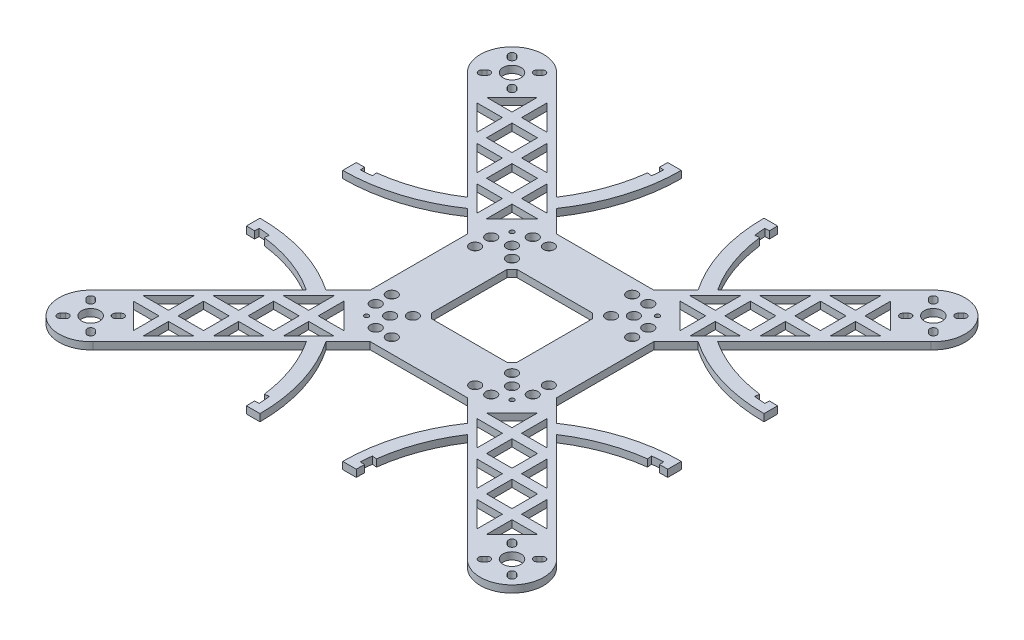
SolidWorks part; units mm, degrees
material "Baltic Birch Plywood"
ref_plane "Front Plane" through (0, 0, 0) normal (0, 0, 1) x (1, 0, 0)
ref_plane "Top Plane" through (0, 0, 0) normal (0, 1, 0) x (1, 0, 0)
ref_plane "Right Plane" through (0, 0, 0) normal (1, 0, 0) x (0, 0, -1)
sketch "Sketch1" plane through (0, 0, 0) normal (0, 1, 0) x (1, 0, 0)
  line L1 (-41.29, -41.29) -> (41.29, -41.29)
  line L2 (-41.29, -41.29) -> (-41.29, 41.29)
  line L3 (-41.29, 41.29) -> (41.29, 41.29)
  line L4 (41.29, -41.29) -> (41.29, 41.29)
  line L5 (-41.29, -41.29) -> (41.29, 41.29) construction
  line L6 (-41.29, 41.29) -> (41.29, -41.29) construction
  point P0 (0, 0)
  dimension "D1" = 82.58
  dimension "D2" = 82.58
extrude "Center Square" add sketch "Sketch1" along normal blind 3.175
sketch "Sketch2" plane through (0, 3.175, 0) normal (0, 1, 0) x (1, 0, 0)
  line L1 (-18.935, -18.935) -> (18.935, -18.935)
  line L2 (-18.935, -18.935) -> (-18.935, 18.935)
  line L3 (-18.935, 18.935) -> (18.935, 18.935)
  line L4 (18.935, -18.935) -> (18.935, 18.935)
  line L5 (-18.935, -18.935) -> (18.935, 18.935) construction
  line L6 (-18.935, 18.935) -> (18.935, -18.935) construction
  point P0 (0, 0)
  dimension "D1" = 37.87
  dimension "D2" = 37.87
extrude "Square Hole" cut sketch "Sketch2" against normal blind 3.175
sketch "Sketch3" plane through (0, 3.175, 0) normal (0, 1, 0) x (1, 0, 0)
  line L0 (0, 0) -> (41.29, 41.29) construction
  line L1 (0, 0) -> (0, 21.955) construction
  line L2 (0, 21.955) -> (21.955, 21.955) construction
  circle A0 centre (21.955, 21.955) radius 2.375
  circle A1 centre (26.9931, 26.9931) radius 2.375
  circle A2 centre (21.955, -21.955) radius 2.375
  circle A3 centre (26.9931, -26.9931) radius 2.375
  circle A4 centre (-21.955, -21.955) radius 2.375
  circle A5 centre (-26.9931, -26.9931) radius 2.375
  circle A6 centre (-21.955, 21.955) radius 2.375
  circle A7 centre (-26.9931, 26.9931) radius 2.375
  point P24 (0, 0)
  dimension "D2" = 4.75
  dimension "D3" = 4.75
  dimension "D1" = 21.955
  dimension "D4" = 7.125
  dimension "D5" = 4
extrude "Power Board Mounting Holes" cut sketch "Sketch3" against normal blind 3.175
sketch "Sketch4" plane through (0, 3.175, 0) normal (0, 1, 0) x (1, 0, 0)
  line L0 (0, 0) -> (18.935, 18.935) construction
  line L1 (16.6899, 18.935) -> (18.935, 16.6899)
  line L2 (18.935, 18.935) -> (17.8125, 17.8125) construction
  line L3 (18.935, -18.935) -> (18.935, 18.935) construction
  line L5 (18.935, 16.6899) -> (18.935, 18.935)
  line L6 (18.935, 18.935) -> (16.6899, 18.935)
  line L7 (18.935, -16.6899) -> (16.6899, -18.935)
  line L9 (16.6899, -18.935) -> (18.935, -18.935)
  line L10 (18.935, -18.935) -> (18.935, -16.6899)
  line L11 (18.935, -18.935) -> (17.8125, -17.8125) construction
  line L12 (-16.6899, -18.935) -> (-18.935, -16.6899)
  line L13 (-18.935, -16.6899) -> (-18.935, -18.935)
  line L14 (-18.935, -18.935) -> (-16.6899, -18.935)
  line L15 (-18.935, -18.935) -> (-17.8125, -17.8125) construction
  line L16 (-18.935, 16.6899) -> (-16.6899, 18.935)
  line L17 (-16.6899, 18.935) -> (-18.935, 18.935)
  line L18 (-18.935, 18.935) -> (-18.935, 16.6899)
  line L19 (-18.935, 18.935) -> (-17.8125, 17.8125) construction
  point P9 (17.8125, 17.8125)
  point P11 (17.8125, 17.8125)
  point P18 (17.8125, -17.8125)
  point P19 (17.8125, -17.8125)
  point P24 (-17.8125, -17.8125)
  point P25 (-17.8125, -17.8125)
  point P30 (-17.8125, 17.8125)
  point P31 (-17.8125, 17.8125)
  point P32 (0, 0)
  dimension "D1" = 1.5875
  dimension "D2" = 4
extrude "Square Hole Diagonals" add sketch "Sketch4" against normal blind 3.175
sketch "Sketch5" plane through (0, 3.175, 0) normal (0, 1, 0) x (1, 0, 0)
  line L0 (0, 0) -> (41.29, 41.29) construction
  line L1 (0, 0) -> (0, 32.22) construction
  line L3 (0, 32.22) -> (32.22, 32.22) construction
  circle A0 centre (32.22, 32.22) radius 1
  circle A1 centre (32.22, -32.22) radius 1
  circle A2 centre (-32.22, -32.22) radius 1
  circle A3 centre (-32.22, 32.22) radius 1
  point P16 (0, 0)
  dimension "D2" = 2
  dimension "D1" = 32.22
  dimension "D3" = 4
extrude "Electronics Board Mounting Holes" cut sketch "Sketch5" against normal through all
sketch "Sketch6" plane through (0, 3.175, 0) normal (0, 1, 0) x (1, 0, 0)
  line L0 (0, 0) -> (41.29, 0) construction
  line L1 (41.29, -41.29) -> (41.29, 41.29) construction
  line L2 (41.29, 0) -> (34.79, 0) construction
  line L3 (34.79, 0) -> (34.79, 18.46) construction
  line L4 (34.79, 18.46) -> (34.79, 25.585) construction
  circle A0 centre (34.79, 18.46) radius 2.375
  circle A1 centre (34.79, 25.585) radius 2.375
  circle A2 centre (34.79, -25.585) radius 2.375
  circle A3 centre (34.79, -18.46) radius 2.375
  circle A4 centre (25.585, -34.79) radius 2.375
  circle A5 centre (18.46, -34.79) radius 2.375
  circle A6 centre (-18.46, -34.79) radius 2.375
  circle A7 centre (-25.585, -34.79) radius 2.375
  circle A8 centre (-34.79, -25.585) radius 2.375
  circle A9 centre (-34.79, -18.46) radius 2.375
  circle A10 centre (-34.79, 18.46) radius 2.375
  circle A11 centre (-34.79, 25.585) radius 2.375
  circle A12 centre (-25.585, 34.79) radius 2.375
  circle A13 centre (-18.46, 34.79) radius 2.375
  circle A14 centre (18.46, 34.79) radius 2.375
  circle A15 centre (25.585, 34.79) radius 2.375
  point P41 (0, 0)
  dimension "D3" = 4.75
  dimension "D4" = 7.125
  dimension "D5" = 4.75
  dimension "D1" = 6.5
  dimension "D2" = 18.46
  dimension "D6" = 4
extrude "IR Sensor Mounting Holes" cut sketch "Sketch6" against normal through all
sketch "Sketch7" plane through (0, 3.175, 0) normal (0, 1, 0) x (1, 0, 0)
  line L0 (33.22, 33.22) -> (93.3241, 93.3241) construction
  line L1 (82.9452, 102.7197) -> (21.5154, 41.29)
  line L2 (41.29, 41.29) -> (-41.29, 41.29) construction
  line L4 (21.5154, 41.29) -> (41.29, 41.29)
  line L5 (41.29, 41.29) -> (41.29, 21.5154)
  line L6 (41.29, -41.29) -> (41.29, 41.29) construction
  line L7 (41.29, 21.5154) -> (102.7197, 82.9452)
  line L8 (102.7197, -82.9452) -> (41.29, -21.5154)
  line L9 (33.22, 33.22) -> (0, 0) construction
  line L10 (21.5154, -41.29) -> (82.9452, -102.7197)
  line L11 (33.22, -33.22) -> (93.3241, -93.3241) construction
  line L12 (41.29, -21.5154) -> (41.29, -41.29)
  line L13 (41.29, -41.29) -> (21.5154, -41.29)
  line L14 (-82.9452, -102.7197) -> (-21.5154, -41.29)
  line L15 (-41.29, -21.5154) -> (-102.7197, -82.9452)
  line L16 (-33.22, -33.22) -> (-93.3241, -93.3241) construction
  line L17 (-21.5154, -41.29) -> (-41.29, -41.29)
  line L18 (-41.29, -41.29) -> (-41.29, -21.5154)
  line L19 (-102.7197, 82.9452) -> (-41.29, 21.5154)
  line L20 (-21.5154, 41.29) -> (-82.9452, 102.7197)
  line L21 (-33.22, 33.22) -> (-93.3241, 93.3241) construction
  line L22 (-41.29, 21.5154) -> (-41.29, 41.29)
  line L23 (-41.29, 41.29) -> (-21.5154, 41.29)
  arc A0 (102.7197, 82.9452) -> (82.9452, 102.7197) centre (93.3241, 93.3241) ccw
  arc A1 (82.9452, -102.7197) -> (102.7197, -82.9452) centre (93.3241, -93.3241) ccw
  arc A2 (-102.7197, -82.9452) -> (-82.9452, -102.7197) centre (-93.3241, -93.3241) ccw
  arc A3 (-82.9452, 102.7197) -> (-102.7197, 82.9452) centre (-93.3241, 93.3241) ccw
  point P38 (0, 0)
  point P45 (0, 0)
  dimension "D2" = 28
  dimension "D1" = 85
extrude "Propeller Arms" add sketch "Sketch7" against normal blind 3.175
sketch "Sketch8" plane through (0, 3.175, 0) normal (0, 1, 0) x (1, 0, 0)
  line L0 (93.3241, 93.3241) -> (103.2236, 103.2236) construction
  line L1 (93.3241, 93.3241) -> (98.9102, 98.9102) construction
  line L2 (93.3241, 93.3241) -> (99.9709, 99.9709) construction
  line L3 (98.9102, 98.9102) -> (99.9709, 99.9709) construction
  line L4 (97.8496, 99.9709) -> (98.9102, 101.0315)
  line L5 (99.9709, 97.8496) -> (101.0315, 98.9102)
  line L6 (98.9102, 87.7379) -> (99.9709, 86.6773) construction
  line L7 (99.9709, 88.7986) -> (101.0315, 87.7379)
  line L8 (97.8496, 86.6773) -> (98.9102, 85.6166)
  line L9 (87.7379, 87.7379) -> (86.6773, 86.6773) construction
  line L10 (88.7986, 86.6773) -> (87.7379, 85.6166)
  line L11 (86.6773, 88.7986) -> (85.6166, 87.7379)
  line L12 (87.7379, 98.9102) -> (86.6773, 99.9709) construction
  line L13 (86.6773, 97.8496) -> (85.6166, 98.9102)
  line L14 (88.7986, 99.9709) -> (87.7379, 101.0315)
  line L15 (93.3241, -93.3241) -> (103.2236, -103.2236) construction
  line L16 (93.3241, -93.3241) -> (98.9102, -98.9102) construction
  line L17 (93.3241, -93.3241) -> (99.9709, -99.9709) construction
  line L18 (98.9102, -98.9102) -> (99.9709, -99.9709) construction
  line L19 (99.9709, -97.8496) -> (101.0315, -98.9102)
  line L20 (97.8496, -99.9709) -> (98.9102, -101.0315)
  line L21 (87.7379, -98.9102) -> (86.6773, -99.9709) construction
  line L22 (88.7986, -99.9709) -> (87.7379, -101.0315)
  line L23 (86.6773, -97.8496) -> (85.6166, -98.9102)
  line L24 (87.7379, -87.7379) -> (86.6773, -86.6773) construction
  line L25 (86.6773, -88.7986) -> (85.6166, -87.7379)
  line L26 (88.7986, -86.6773) -> (87.7379, -85.6166)
  line L27 (98.9102, -87.7379) -> (99.9709, -86.6773) construction
  line L28 (97.8496, -86.6773) -> (98.9102, -85.6166)
  line L29 (99.9709, -88.7986) -> (101.0315, -87.7379)
  line L30 (-93.3241, -93.3241) -> (-103.2236, -103.2236) construction
  line L31 (-93.3241, -93.3241) -> (-98.9102, -98.9102) construction
  line L32 (-93.3241, -93.3241) -> (-99.9709, -99.9709) construction
  line L33 (-98.9102, -98.9102) -> (-99.9709, -99.9709) construction
  line L34 (-97.8496, -99.9709) -> (-98.9102, -101.0315)
  line L35 (-99.9709, -97.8496) -> (-101.0315, -98.9102)
  line L36 (-98.9102, -87.7379) -> (-99.9709, -86.6773) construction
  line L37 (-99.9709, -88.7986) -> (-101.0315, -87.7379)
  line L38 (-97.8496, -86.6773) -> (-98.9102, -85.6166)
  line L39 (-87.7379, -87.7379) -> (-86.6773, -86.6773) construction
  line L40 (-88.7986, -86.6773) -> (-87.7379, -85.6166)
  line L41 (-86.6773, -88.7986) -> (-85.6166, -87.7379)
  line L42 (-87.7379, -98.9102) -> (-86.6773, -99.9709) construction
  line L43 (-86.6773, -97.8496) -> (-85.6166, -98.9102)
  line L44 (-88.7986, -99.9709) -> (-87.7379, -101.0315)
  line L45 (-93.3241, 93.3241) -> (-103.2236, 103.2236) construction
  line L46 (-93.3241, 93.3241) -> (-98.9102, 98.9102) construction
  line L47 (-93.3241, 93.3241) -> (-99.9709, 99.9709) construction
  line L48 (-98.9102, 98.9102) -> (-99.9709, 99.9709) construction
  line L49 (-99.9709, 97.8496) -> (-101.0315, 98.9102)
  line L50 (-97.8496, 99.9709) -> (-98.9102, 101.0315)
  line L51 (-87.7379, 98.9102) -> (-86.6773, 99.9709) construction
  line L52 (-88.7986, 99.9709) -> (-87.7379, 101.0315)
  line L53 (-86.6773, 97.8496) -> (-85.6166, 98.9102)
  line L54 (-87.7379, 87.7379) -> (-86.6773, 86.6773) construction
  line L55 (-86.6773, 88.7986) -> (-85.6166, 87.7379)
  line L56 (-88.7986, 86.6773) -> (-87.7379, 85.6166)
  line L57 (-98.9102, 87.7379) -> (-99.9709, 86.6773) construction
  line L58 (-97.8496, 86.6773) -> (-98.9102, 85.6166)
  line L59 (-99.9709, 88.7986) -> (-101.0315, 87.7379)
  circle A0 centre (93.3241, 93.3241) radius 4
  arc A1 (102.7197, 82.9452) -> (82.9452, 102.7197) centre (93.3241, 93.3241) ccw construction
  arc A2 (97.8496, 99.9709) -> (99.9709, 97.8496) centre (98.9102, 98.9102) ccw
  arc A3 (101.0315, 98.9102) -> (98.9102, 101.0315) centre (99.9709, 99.9709) ccw
  arc A4 (99.9709, 88.7986) -> (97.8496, 86.6773) centre (98.9102, 87.7379) ccw
  arc A5 (98.9102, 85.6166) -> (101.0315, 87.7379) centre (99.9709, 86.6773) ccw
  arc A6 (88.7986, 86.6773) -> (86.6773, 88.7986) centre (87.7379, 87.7379) ccw
  arc A7 (85.6166, 87.7379) -> (87.7379, 85.6166) centre (86.6773, 86.6773) ccw
  arc A8 (86.6773, 97.8496) -> (88.7986, 99.9709) centre (87.7379, 98.9102) ccw
  arc A9 (87.7379, 101.0315) -> (85.6166, 98.9102) centre (86.6773, 99.9709) ccw
  circle A10 centre (93.3241, -93.3241) radius 4
  arc A11 (99.9709, -97.8496) -> (97.8496, -99.9709) centre (98.9102, -98.9102) ccw
  arc A12 (98.9102, -101.0315) -> (101.0315, -98.9102) centre (99.9709, -99.9709) ccw
  arc A13 (88.7986, -99.9709) -> (86.6773, -97.8496) centre (87.7379, -98.9102) ccw
  arc A14 (85.6166, -98.9102) -> (87.7379, -101.0315) centre (86.6773, -99.9709) ccw
  arc A15 (86.6773, -88.7986) -> (88.7986, -86.6773) centre (87.7379, -87.7379) ccw
  arc A16 (87.7379, -85.6166) -> (85.6166, -87.7379) centre (86.6773, -86.6773) ccw
  arc A17 (97.8496, -86.6773) -> (99.9709, -88.7986) centre (98.9102, -87.7379) ccw
  arc A18 (101.0315, -87.7379) -> (98.9102, -85.6166) centre (99.9709, -86.6773) ccw
  circle A19 centre (-93.3241, -93.3241) radius 4
  arc A20 (-97.8496, -99.9709) -> (-99.9709, -97.8496) centre (-98.9102, -98.9102) ccw
  arc A21 (-101.0315, -98.9102) -> (-98.9102, -101.0315) centre (-99.9709, -99.9709) ccw
  arc A22 (-99.9709, -88.7986) -> (-97.8496, -86.6773) centre (-98.9102, -87.7379) ccw
  arc A23 (-98.9102, -85.6166) -> (-101.0315, -87.7379) centre (-99.9709, -86.6773) ccw
  arc A24 (-88.7986, -86.6773) -> (-86.6773, -88.7986) centre (-87.7379, -87.7379) ccw
  arc A25 (-85.6166, -87.7379) -> (-87.7379, -85.6166) centre (-86.6773, -86.6773) ccw
  arc A26 (-86.6773, -97.8496) -> (-88.7986, -99.9709) centre (-87.7379, -98.9102) ccw
  arc A27 (-87.7379, -101.0315) -> (-85.6166, -98.9102) centre (-86.6773, -99.9709) ccw
  circle A28 centre (-93.3241, 93.3241) radius 4
  arc A29 (-99.9709, 97.8496) -> (-97.8496, 99.9709) centre (-98.9102, 98.9102) ccw
  arc A30 (-98.9102, 101.0315) -> (-101.0315, 98.9102) centre (-99.9709, 99.9709) ccw
  arc A31 (-88.7986, 99.9709) -> (-86.6773, 97.8496) centre (-87.7379, 98.9102) ccw
  arc A32 (-85.6166, 98.9102) -> (-87.7379, 101.0315) centre (-86.6773, 99.9709) ccw
  arc A33 (-86.6773, 88.7986) -> (-88.7986, 86.6773) centre (-87.7379, 87.7379) ccw
  arc A34 (-87.7379, 85.6166) -> (-85.6166, 87.7379) centre (-86.6773, 86.6773) ccw
  arc A35 (-97.8496, 86.6773) -> (-99.9709, 88.7986) centre (-98.9102, 87.7379) ccw
  arc A36 (-101.0315, 87.7379) -> (-98.9102, 85.6166) centre (-99.9709, 86.6773) ccw
  point P7 (99.4406, 99.4406)
  point P17 (99.4406, 87.2076)
  point P24 (87.2076, 87.2076)
  point P31 (87.2076, 99.4406)
  point P38 (93.3241, 93.3241)
  point P42 (99.4406, -99.4406)
  point P49 (87.2076, -99.4406)
  point P56 (87.2076, -87.2076)
  point P63 (99.4406, -87.2076)
  point P70 (93.3241, -93.3241)
  point P74 (-99.4406, -99.4406)
  point P81 (-99.4406, -87.2076)
  point P88 (-87.2076, -87.2076)
  point P95 (-87.2076, -99.4406)
  point P102 (-93.3241, -93.3241)
  point P106 (-99.4406, 99.4406)
  point P113 (-87.2076, 99.4406)
  point P120 (-87.2076, 87.2076)
  point P127 (-99.4406, 87.2076)
  point P134 (-93.3241, 93.3241)
  point P135 (0, 0)
  dimension "D5" = 4
  dimension "D1" = 8
  dimension "D4" = 1.5
  dimension "D2" = 7.9
  dimension "D3" = 9.4
extrude "Motor Mounting Holes" cut sketch "Sketch8" against normal through all
sketch "Sketch10" plane through (0, 3.175, 0) normal (0, 1, 0) x (1, 0, 0)
  line L0 (0, 0) -> (93.3241, 93.3241) construction
  line L1 (32.22, 32.22) -> (37.2581, 37.2581) construction
  line L2 (31.6135, 42.9028) -> (42.9028, 31.6135)
  line L3 (41.29, 21.5154) -> (102.7197, 82.9452) construction
  line L4 (42.9028, 31.6135) -> (42.9028, 42.9028)
  line L5 (42.9028, 42.9028) -> (31.6135, 42.9028)
  line L6 (42.9028, 31.6135) -> (47.1484, 31.6135) construction
  line L7 (47.1484, 31.6135) -> (49.348, 29.5734) construction
  line L8 (45.0256, 31.6135) -> (45.0256, 45.0256) construction
  line L9 (42.9028, 47.1484) -> (42.9028, 58.4377)
  line L10 (42.9028, 58.4377) -> (31.6135, 47.1484)
  line L11 (31.6135, 47.1484) -> (42.9028, 47.1484)
  line L12 (47.1484, 47.1484) -> (58.4377, 47.1484)
  line L13 (47.1484, 58.4377) -> (58.4377, 58.4377)
  line L14 (47.1484, 58.4377) -> (47.1484, 47.1484)
  line L15 (47.1484, 42.9028) -> (47.1484, 31.6135)
  line L16 (47.1484, 31.6135) -> (58.4377, 42.9028)
  line L17 (58.4377, 42.9028) -> (47.1484, 42.9028)
  line L18 (58.4377, 47.1484) -> (47.1484, 58.4377) [skipped]
  line L19 (58.4377, 58.4377) -> (58.4377, 47.1484)
  line L20 (58.4377, 42.9028) -> (62.6773, 42.9028) construction
  line L21 (60.5575, 42.9028) -> (60.5575, 60.5575) construction
  line L22 (45.0256, 45.0256) -> (60.5575, 45.0256) construction
  line L24 (60.5575, 60.5575) -> (45.0256, 60.5575) construction
  line L25 (45.0256, 60.5575) -> (45.0256, 45.0256) construction
  line L26 (58.4328, 47.1484) -> (58.4328, 58.4377) [skipped]
  line L27 (58.4328, 58.4377) -> (47.1435, 47.1484) [skipped]
  line L28 (47.1435, 47.1484) -> (58.4328, 47.1484) [skipped]
  line L29 (62.6784, 58.4377) -> (62.6784, 47.1484) [skipped]
  line L30 (62.6784, 58.4377) -> (73.9677, 58.4377) [skipped]
  line L31 (73.9677, 58.4377) -> (73.9677, 47.1484) [skipped]
  line L32 (62.6784, 47.1484) -> (73.9677, 47.1484) [skipped]
  line L33 (73.9677, 42.9028) -> (62.6784, 42.9028) [skipped]
  line L34 (62.6784, 42.9028) -> (62.6784, 31.6135) [skipped]
  line L35 (62.6784, 31.6135) -> (73.9677, 42.9028) [skipped]
  line L36 (73.9628, 47.1484) -> (73.9628, 58.4377) [skipped]
  line L37 (73.9628, 58.4377) -> (62.6735, 47.1484) [skipped]
  line L38 (62.6735, 47.1484) -> (73.9628, 47.1484) [skipped]
  line L39 (78.2084, 58.4377) -> (78.2084, 47.1484) [skipped]
  line L40 (78.2084, 58.4377) -> (89.4977, 58.4377) [skipped]
  line L41 (89.4977, 58.4377) -> (89.4977, 47.1484) [skipped]
  line L42 (78.2084, 47.1484) -> (89.4977, 47.1484) [skipped]
  line L43 (89.4977, 42.9028) -> (78.2084, 42.9028) [skipped]
  line L44 (78.2084, 42.9028) -> (78.2084, 31.6135) [skipped]
  line L45 (78.2084, 31.6135) -> (89.4977, 42.9028) [skipped]
  line L46 (58.4328, 62.6784) -> (58.4328, 73.9677)
  line L47 (58.4328, 73.9677) -> (47.1435, 62.6784)
  line L48 (47.1435, 62.6784) -> (58.4328, 62.6784)
  line L49 (62.6784, 73.9677) -> (62.6784, 62.6784)
  line L50 (62.6784, 73.9677) -> (73.9677, 73.9677)
  line L51 (73.9677, 73.9677) -> (73.9677, 62.6784)
  line L52 (62.6784, 62.6784) -> (73.9677, 62.6784)
  line L53 (73.9677, 58.4328) -> (62.6784, 58.4328)
  line L54 (62.6784, 58.4328) -> (62.6784, 47.1435)
  line L55 (62.6784, 47.1435) -> (73.9677, 58.4328)
  line L56 (73.9628, 62.6784) -> (73.9628, 73.9677) [skipped]
  line L57 (73.9628, 73.9677) -> (62.6735, 62.6784) [skipped]
  line L58 (62.6735, 62.6784) -> (73.9628, 62.6784) [skipped]
  line L59 (78.2084, 73.9677) -> (78.2084, 62.6784) [skipped]
  line L60 (78.2084, 73.9677) -> (89.4977, 73.9677) [skipped]
  line L61 (89.4977, 73.9677) -> (89.4977, 62.6784) [skipped]
  line L62 (78.2084, 62.6784) -> (89.4977, 62.6784) [skipped]
  line L63 (89.4977, 58.4328) -> (78.2084, 58.4328) [skipped]
  line L64 (78.2084, 58.4328) -> (78.2084, 47.1435) [skipped]
  line L65 (78.2084, 47.1435) -> (89.4977, 58.4328) [skipped]
  line L66 (58.4328, 78.2084) -> (58.4328, 89.4977) [skipped]
  line L67 (58.4328, 89.4977) -> (47.1435, 78.2084) [skipped]
  line L68 (47.1435, 78.2084) -> (58.4328, 78.2084) [skipped]
  line L69 (62.6784, 89.4977) -> (62.6784, 78.2084) [skipped]
  line L70 (62.6784, 89.4977) -> (73.9677, 89.4977) [skipped]
  line L71 (73.9677, 89.4977) -> (73.9677, 78.2084) [skipped]
  line L72 (62.6784, 78.2084) -> (73.9677, 78.2084) [skipped]
  line L73 (73.9677, 73.9628) -> (62.6784, 73.9628) [skipped]
  line L74 (62.6784, 73.9628) -> (62.6784, 62.6735) [skipped]
  line L75 (62.6784, 62.6735) -> (73.9677, 73.9628) [skipped]
  line L76 (73.9628, 78.2084) -> (73.9628, 89.4977)
  line L77 (73.9628, 89.4977) -> (62.6735, 78.2084)
  line L78 (62.6735, 78.2084) -> (73.9628, 78.2084)
  line L79 (78.2084, 89.4977) -> (78.2084, 78.2084)
  line L80 (78.2084, 89.4977) -> (89.4977, 78.2084)
  line L81 (42.9028, -31.6135) -> (31.6135, -42.9028)
  line L82 (78.2084, 78.2084) -> (89.4977, 78.2084)
  line L83 (89.4977, 73.9628) -> (78.2084, 73.9628)
  line L84 (78.2084, 73.9628) -> (78.2084, 62.6735)
  line L85 (78.2084, 62.6735) -> (89.4977, 73.9628)
  line L86 (42.9028, 62.6784) -> (42.9028, 73.9677) [skipped]
  line L87 (42.9028, 73.9677) -> (31.6135, 62.6784) [skipped]
  line L88 (31.6135, 62.6784) -> (42.9028, 62.6784) [skipped]
  line L89 (47.1484, 73.9677) -> (47.1484, 62.6784) [skipped]
  line L90 (47.1484, 73.9677) -> (58.4377, 73.9677) [skipped]
  line L91 (58.4377, 73.9677) -> (58.4377, 62.6784) [skipped]
  line L92 (47.1484, 62.6784) -> (58.4377, 62.6784) [skipped]
  line L93 (58.4377, 58.4328) -> (47.1484, 58.4328) [skipped]
  line L94 (47.1484, 58.4328) -> (47.1484, 47.1435) [skipped]
  line L95 (47.1484, 47.1435) -> (58.4377, 58.4328) [skipped]
  line L96 (42.9028, 78.2084) -> (42.9028, 89.4977) [skipped]
  line L97 (42.9028, 89.4977) -> (31.6135, 78.2084) [skipped]
  line L98 (31.6135, 78.2084) -> (42.9028, 78.2084) [skipped]
  line L99 (47.1484, 89.4977) -> (47.1484, 78.2084) [skipped]
  line L100 (47.1484, 89.4977) -> (58.4377, 89.4977) [skipped]
  line L101 (58.4377, 89.4977) -> (58.4377, 78.2084) [skipped]
  line L102 (47.1484, 78.2084) -> (58.4377, 78.2084) [skipped]
  line L103 (58.4377, 73.9628) -> (47.1484, 73.9628) [skipped]
  line L104 (47.1484, 73.9628) -> (47.1484, 62.6735) [skipped]
  line L105 (47.1484, 62.6735) -> (58.4377, 73.9628) [skipped]
  line L106 (78.2084, 89.4977) -> (89.4977, 89.4977) [skipped]
  line L107 (89.4977, 89.4977) -> (89.4977, 78.2084) [skipped]
  line L108 (31.6135, -42.9028) -> (42.9028, -42.9028)
  line L109 (42.9028, -42.9028) -> (42.9028, -31.6135)
  line L110 (47.1484, -42.9028) -> (58.4377, -42.9028)
  line L111 (58.4377, -42.9028) -> (47.1484, -31.6135)
  line L112 (47.1484, -31.6135) -> (47.1484, -42.9028)
  line L113 (47.1484, -47.1484) -> (47.1484, -58.4377)
  line L114 (58.4377, -47.1484) -> (58.4377, -58.4377)
  line L115 (58.4377, -47.1484) -> (47.1484, -47.1484)
  line L116 (42.9028, -47.1484) -> (31.6135, -47.1484)
  line L117 (31.6135, -47.1484) -> (42.9028, -58.4377)
  line L118 (42.9028, -58.4377) -> (42.9028, -47.1484)
  line L119 (58.4377, -58.4377) -> (47.1484, -58.4377)
  line L120 (62.6784, -58.4328) -> (73.9677, -58.4328)
  line L121 (73.9677, -58.4328) -> (62.6784, -47.1435)
  line L122 (62.6784, -47.1435) -> (62.6784, -58.4328)
  line L123 (73.9677, -62.6784) -> (62.6784, -62.6784)
  line L124 (73.9677, -62.6784) -> (73.9677, -73.9677)
  line L125 (73.9677, -73.9677) -> (62.6784, -73.9677)
  line L126 (62.6784, -62.6784) -> (62.6784, -73.9677)
  line L127 (58.4328, -73.9677) -> (58.4328, -62.6784)
  line L128 (58.4328, -62.6784) -> (47.1435, -62.6784)
  line L129 (47.1435, -62.6784) -> (58.4328, -73.9677)
  line L130 (78.2084, -73.9628) -> (89.4977, -73.9628)
  line L131 (89.4977, -73.9628) -> (78.2084, -62.6735)
  line L132 (78.2084, -62.6735) -> (78.2084, -73.9628)
  line L133 (89.4977, -78.2084) -> (78.2084, -78.2084)
  line L134 (89.4977, -78.2084) -> (78.2084, -89.4977)
  line L135 (78.2084, -78.2084) -> (78.2084, -89.4977)
  line L136 (73.9628, -89.4977) -> (73.9628, -78.2084)
  line L137 (73.9628, -78.2084) -> (62.6735, -78.2084)
  line L138 (62.6735, -78.2084) -> (73.9628, -89.4977)
  line L139 (32.22, -32.22) -> (37.2581, -37.2581) construction
  line L140 (31.6135, -42.9028) -> (31.6135, -47.1484) construction
  line L141 (31.6135, -47.1484) -> (29.5734, -49.348) construction
  line L142 (31.6135, -45.0256) -> (45.0256, -45.0256) construction
  line L143 (42.9028, -58.4377) -> (42.9028, -62.6773) construction
  line L144 (42.9028, -60.5575) -> (60.5575, -60.5575) construction
  line L145 (45.0256, -45.0256) -> (45.0256, -60.5575) construction
  line L146 (60.5575, -60.5575) -> (60.5575, -45.0256) construction
  line L147 (60.5575, -45.0256) -> (45.0256, -45.0256) construction
  line L148 (-31.6135, -42.9028) -> (-42.9028, -31.6135)
  line L149 (-42.9028, -31.6135) -> (-42.9028, -42.9028)
  line L150 (-42.9028, -42.9028) -> (-31.6135, -42.9028)
  line L151 (-42.9028, -47.1484) -> (-42.9028, -58.4377)
  line L152 (-42.9028, -58.4377) -> (-31.6135, -47.1484)
  line L153 (-31.6135, -47.1484) -> (-42.9028, -47.1484)
  line L154 (-47.1484, -47.1484) -> (-58.4377, -47.1484)
  line L155 (-47.1484, -58.4377) -> (-58.4377, -58.4377)
  line L156 (-47.1484, -58.4377) -> (-47.1484, -47.1484)
  line L157 (-47.1484, -42.9028) -> (-47.1484, -31.6135)
  line L158 (-47.1484, -31.6135) -> (-58.4377, -42.9028)
  line L159 (-58.4377, -42.9028) -> (-47.1484, -42.9028)
  line L160 (-58.4377, -58.4377) -> (-58.4377, -47.1484)
  line L161 (-58.4328, -62.6784) -> (-58.4328, -73.9677)
  line L162 (-58.4328, -73.9677) -> (-47.1435, -62.6784)
  line L163 (-47.1435, -62.6784) -> (-58.4328, -62.6784)
  line L164 (-62.6784, -73.9677) -> (-62.6784, -62.6784)
  line L165 (-62.6784, -73.9677) -> (-73.9677, -73.9677)
  line L166 (-73.9677, -73.9677) -> (-73.9677, -62.6784)
  line L167 (-62.6784, -62.6784) -> (-73.9677, -62.6784)
  line L168 (-73.9677, -58.4328) -> (-62.6784, -58.4328)
  line L169 (-62.6784, -58.4328) -> (-62.6784, -47.1435)
  line L170 (-62.6784, -47.1435) -> (-73.9677, -58.4328)
  line L171 (-73.9628, -78.2084) -> (-73.9628, -89.4977)
  line L172 (-73.9628, -89.4977) -> (-62.6735, -78.2084)
  line L173 (-62.6735, -78.2084) -> (-73.9628, -78.2084)
  line L174 (-78.2084, -89.4977) -> (-78.2084, -78.2084)
  line L175 (-78.2084, -89.4977) -> (-89.4977, -78.2084)
  line L176 (-78.2084, -78.2084) -> (-89.4977, -78.2084)
  line L177 (-89.4977, -73.9628) -> (-78.2084, -73.9628)
  line L178 (-78.2084, -73.9628) -> (-78.2084, -62.6735)
  line L179 (-78.2084, -62.6735) -> (-89.4977, -73.9628)
  line L180 (-32.22, -32.22) -> (-37.2581, -37.2581) construction
  line L181 (-42.9028, -31.6135) -> (-47.1484, -31.6135) construction
  line L182 (-47.1484, -31.6135) -> (-49.348, -29.5734) construction
  line L183 (-45.0256, -31.6135) -> (-45.0256, -45.0256) construction
  line L184 (-58.4377, -42.9028) -> (-62.6773, -42.9028) construction
  line L185 (-60.5575, -42.9028) -> (-60.5575, -60.5575) construction
  line L186 (-45.0256, -45.0256) -> (-60.5575, -45.0256) construction
  line L187 (-60.5575, -60.5575) -> (-45.0256, -60.5575) construction
  line L188 (-45.0256, -60.5575) -> (-45.0256, -45.0256) construction
  line L189 (-42.9028, 31.6135) -> (-31.6135, 42.9028)
  line L190 (-31.6135, 42.9028) -> (-42.9028, 42.9028)
  line L191 (-42.9028, 42.9028) -> (-42.9028, 31.6135)
  line L192 (-47.1484, 42.9028) -> (-58.4377, 42.9028)
  line L193 (-58.4377, 42.9028) -> (-47.1484, 31.6135)
  line L194 (-47.1484, 31.6135) -> (-47.1484, 42.9028)
  line L195 (-47.1484, 47.1484) -> (-47.1484, 58.4377)
  line L196 (-58.4377, 47.1484) -> (-58.4377, 58.4377)
  line L197 (-58.4377, 47.1484) -> (-47.1484, 47.1484)
  line L198 (-42.9028, 47.1484) -> (-31.6135, 47.1484)
  line L199 (-31.6135, 47.1484) -> (-42.9028, 58.4377)
  line L200 (-42.9028, 58.4377) -> (-42.9028, 47.1484)
  line L201 (-58.4377, 58.4377) -> (-47.1484, 58.4377)
  line L202 (-62.6784, 58.4328) -> (-73.9677, 58.4328)
  line L203 (-73.9677, 58.4328) -> (-62.6784, 47.1435)
  line L204 (-62.6784, 47.1435) -> (-62.6784, 58.4328)
  line L205 (-73.9677, 62.6784) -> (-62.6784, 62.6784)
  line L206 (-73.9677, 62.6784) -> (-73.9677, 73.9677)
  line L207 (-73.9677, 73.9677) -> (-62.6784, 73.9677)
  line L208 (-62.6784, 62.6784) -> (-62.6784, 73.9677)
  line L209 (-58.4328, 73.9677) -> (-58.4328, 62.6784)
  line L210 (-58.4328, 62.6784) -> (-47.1435, 62.6784)
  line L211 (-47.1435, 62.6784) -> (-58.4328, 73.9677)
  line L212 (-78.2084, 73.9628) -> (-89.4977, 73.9628)
  line L213 (-89.4977, 73.9628) -> (-78.2084, 62.6735)
  line L214 (-78.2084, 62.6735) -> (-78.2084, 73.9628)
  line L215 (-89.4977, 78.2084) -> (-78.2084, 78.2084)
  line L216 (-89.4977, 78.2084) -> (-78.2084, 89.4977)
  line L217 (-78.2084, 78.2084) -> (-78.2084, 89.4977)
  line L218 (-73.9628, 89.4977) -> (-73.9628, 78.2084)
  line L219 (-73.9628, 78.2084) -> (-62.6735, 78.2084)
  line L220 (-62.6735, 78.2084) -> (-73.9628, 89.4977)
  line L221 (-32.22, 32.22) -> (-37.2581, 37.2581) construction
  line L222 (-31.6135, 42.9028) -> (-31.6135, 47.1484) construction
  line L223 (-31.6135, 47.1484) -> (-29.5734, 49.348) construction
  line L224 (-31.6135, 45.0256) -> (-45.0256, 45.0256) construction
  line L225 (-42.9028, 58.4377) -> (-42.9028, 62.6773) construction
  line L226 (-42.9028, 60.5575) -> (-60.5575, 60.5575) construction
  line L227 (-45.0256, 45.0256) -> (-45.0256, 60.5575) construction
  line L228 (-60.5575, 60.5575) -> (-60.5575, 45.0256) construction
  line L229 (-60.5575, 45.0256) -> (-45.0256, 45.0256) construction
  point P10 (37.2581, 37.2581)
  point P29 (45.0256, 45.0256)
  point P125 (37.2581, -37.2581)
  point P143 (45.0256, -45.0256)
  point P170 (-37.2581, -37.2581)
  point P188 (-45.0256, -45.0256)
  point P215 (-37.2581, 37.2581)
  point P233 (-45.0256, 45.0256)
  point P256 (0, 0)
  dimension "D1" = 7.125
  dimension "D2" = 6
  dimension "D3" = 3
  dimension "D5" = 3
  dimension "D6" = 3
  dimension "D4" = 4
extrude "Arm Cross-Hatching" cut sketch "Sketch10" against normal through all
sketch "Sketch11" plane through (0, 3.175, 0) normal (0, 1, 0) x (1, 0, 0)
  line L0 (0, 0) -> (93.3241, 93.3241) construction
  line L1 (93.3241, 93.3241) -> (0, 93.3241) construction
  line L2 (0, 93.3241) -> (0, 0) construction
  line L3 (21.5154, 41.29) -> (52.2303, 72.0049) construction
  line L4 (82.9452, 102.7197) -> (21.5154, 41.29) construction
  line L5 (18.3241, 93.3241) -> (24.3241, 93.3241)
  line L6 (31.3336, 51.1082) -> (35.6588, 55.4333)
  line L7 (93.3241, 93.3241) -> (18.4269, 89.3989) construction
  line L8 (93.3241, 93.3241) -> (18.8831, 84.1839) construction
  line L9 (22.4214, 89.6082) -> (24.4186, 89.7129)
  line L10 (22.8533, 84.6714) -> (24.8384, 84.9151)
  line L11 (84.6714, 22.8533) -> (84.9151, 24.8384)
  line L12 (89.6082, 22.4214) -> (89.7129, 24.4186)
  line L13 (51.1082, 31.3336) -> (55.4333, 35.6588)
  line L14 (93.3241, 18.3241) -> (93.3241, 24.3241)
  line L15 (93.3241, -18.3241) -> (93.3241, -24.3241)
  line L16 (51.1082, -31.3336) -> (55.4333, -35.6588)
  line L17 (89.6082, -22.4214) -> (89.7129, -24.4186)
  line L18 (84.6714, -22.8533) -> (84.9151, -24.8384)
  line L19 (22.8533, -84.6714) -> (24.8384, -84.9151)
  line L20 (22.4214, -89.6082) -> (24.4186, -89.7129)
  line L21 (31.3336, -51.1082) -> (35.6588, -55.4333)
  line L22 (18.3241, -93.3241) -> (24.3241, -93.3241)
  line L23 (-18.3241, -93.3241) -> (-24.3241, -93.3241)
  line L24 (-31.3336, -51.1082) -> (-35.6588, -55.4333)
  line L25 (-22.4214, -89.6082) -> (-24.4186, -89.7129)
  line L26 (-22.8533, -84.6714) -> (-24.8384, -84.9151)
  line L27 (-84.6714, -22.8533) -> (-84.9151, -24.8384)
  line L28 (-89.6082, -22.4214) -> (-89.7129, -24.4186)
  line L29 (-51.1082, -31.3336) -> (-55.4333, -35.6588)
  line L30 (-93.3241, -18.3241) -> (-93.3241, -24.3241)
  line L31 (-93.3241, 18.3241) -> (-93.3241, 24.3241)
  line L32 (-51.1082, 31.3336) -> (-55.4333, 35.6588)
  line L33 (-89.6082, 22.4214) -> (-89.7129, 24.4186)
  line L34 (-84.6714, 22.8533) -> (-84.9151, 24.8384)
  line L35 (-22.8533, 84.6714) -> (-24.8384, 84.9151)
  line L36 (-22.4214, 89.6082) -> (-24.4186, 89.7129)
  line L37 (-31.3336, 51.1082) -> (-35.6588, 55.4333)
  line L38 (-18.3241, 93.3241) -> (-24.3241, 93.3241)
  arc A0 (18.3241, 93.3241) -> (31.3336, 51.1082) centre (93.3241, 93.3241) ccw
  arc A1 (24.3241, 93.3241) -> (24.4186, 89.7129) centre (93.3241, 93.3241) ccw
  arc A2 (22.4214, 89.6082) -> (22.8533, 84.6714) centre (93.3241, 93.3241) ccw
  arc A3 (24.8384, 84.9151) -> (35.6588, 55.4333) centre (93.3241, 93.3241) ccw
  arc A4 (84.9151, 24.8384) -> (55.4333, 35.6588) centre (93.3241, 93.3241) cw
  arc A5 (89.6082, 22.4214) -> (84.6714, 22.8533) centre (93.3241, 93.3241) cw
  arc A6 (93.3241, 24.3241) -> (89.7129, 24.4186) centre (93.3241, 93.3241) cw
  arc A7 (93.3241, 18.3241) -> (51.1082, 31.3336) centre (93.3241, 93.3241) cw
  arc A8 (93.3241, -18.3241) -> (51.1082, -31.3336) centre (93.3241, -93.3241) ccw
  arc A9 (93.3241, -24.3241) -> (89.7129, -24.4186) centre (93.3241, -93.3241) ccw
  arc A10 (89.6082, -22.4214) -> (84.6714, -22.8533) centre (93.3241, -93.3241) ccw
  arc A11 (84.9151, -24.8384) -> (55.4333, -35.6588) centre (93.3241, -93.3241) ccw
  arc A12 (24.8384, -84.9151) -> (35.6588, -55.4333) centre (93.3241, -93.3241) cw
  arc A13 (22.4214, -89.6082) -> (22.8533, -84.6714) centre (93.3241, -93.3241) cw
  arc A14 (24.3241, -93.3241) -> (24.4186, -89.7129) centre (93.3241, -93.3241) cw
  arc A15 (18.3241, -93.3241) -> (31.3336, -51.1082) centre (93.3241, -93.3241) cw
  arc A16 (-18.3241, -93.3241) -> (-31.3336, -51.1082) centre (-93.3241, -93.3241) ccw
  arc A17 (-24.3241, -93.3241) -> (-24.4186, -89.7129) centre (-93.3241, -93.3241) ccw
  arc A18 (-22.4214, -89.6082) -> (-22.8533, -84.6714) centre (-93.3241, -93.3241) ccw
  arc A19 (-24.8384, -84.9151) -> (-35.6588, -55.4333) centre (-93.3241, -93.3241) ccw
  arc A20 (-84.9151, -24.8384) -> (-55.4333, -35.6588) centre (-93.3241, -93.3241) cw
  arc A21 (-89.6082, -22.4214) -> (-84.6714, -22.8533) centre (-93.3241, -93.3241) cw
  arc A22 (-93.3241, -24.3241) -> (-89.7129, -24.4186) centre (-93.3241, -93.3241) cw
  arc A23 (-93.3241, -18.3241) -> (-51.1082, -31.3336) centre (-93.3241, -93.3241) cw
  arc A24 (-93.3241, 18.3241) -> (-51.1082, 31.3336) centre (-93.3241, 93.3241) ccw
  arc A25 (-93.3241, 24.3241) -> (-89.7129, 24.4186) centre (-93.3241, 93.3241) ccw
  arc A26 (-89.6082, 22.4214) -> (-84.6714, 22.8533) centre (-93.3241, 93.3241) ccw
  arc A27 (-84.9151, 24.8384) -> (-55.4333, 35.6588) centre (-93.3241, 93.3241) ccw
  arc A28 (-24.8384, 84.9151) -> (-35.6588, 55.4333) centre (-93.3241, 93.3241) cw
  arc A29 (-22.4214, 89.6082) -> (-22.8533, 84.6714) centre (-93.3241, 93.3241) cw
  arc A30 (-24.3241, 93.3241) -> (-24.4186, 89.7129) centre (-93.3241, 93.3241) cw
  arc A31 (-18.3241, 93.3241) -> (-31.3336, 51.1082) centre (-93.3241, 93.3241) cw
  point P79 (0, 0)
  dimension "D1" = 150
  dimension "D2" = 138
  dimension "D3" = 142
extrude "Guard Rings" add sketch "Sketch11" against normal blind 3.175
equation "\"breadBoardLength\"= 82.58'change back to 82.58"
equation "\"D1@Sketch1\"=\"breadBoardLength\""
equation "\"D2@Sketch1\"=\"breadBoardLength\""
equation "\"powerBoardFoamWidth\"=37.87"
equation "\"D1@Sketch2\"=\"powerBoardFoamWidth\""
equation "\"D2@Sketch2\"=\"powerBoardFoamWidth\""
equation "\"powerBoardHoleDistance\"=21.955"
equation "\"D1@Sketch3\"=\"powerBoardHoleDistance\""
equation "\"zipTieHoleDiameter\"=4.75"
equation "\"D2@Sketch3\"=\"zipTieHoleDiameter\""
equation "\"D3@Sketch3\"=\"zipTieHoleDiameter\""
equation "\"D4@Sketch3\"=\"zipTieHoleDiameter\"*1.5"
equation "\"woodThickness\"=3.175"
equation "\"D1@Sketch4\"=\"woodThickness\"/2"
equation "\"D1@Sketch5\"=\"electronicsMountDistance\""
equation "\"electronicsMountDistance\"=32.22"
equation "\"standoffHoleDiameter\"=2"
equation "\"D2@Sketch5\"=\"standoffHoleDiameter\""
equation "\"irWidth\"=13"
equation "\"D1@Sketch6\"=\"irWidth\"/2"
equation "\"irHoleToHole\"=36.92"
equation "\"D2@Sketch6\"=\"irHoleToHole\"/2"
equation "\"D3@Sketch6\"=\"zipTieHoleDiameter\""
equation "\"D4@Sketch6\"=\"zipTieHoleDiameter\"*1.5"
equation "\"D5@Sketch6\"=\"zipTieHoleDiameter\""
equation "\"guardOuterDiameter\"=170"
equation "\"D1@Sketch7\"=\"guardOuterDiameter\"/2"
equation "\"motorDiameter\"=28"
equation "\"D2@Sketch7\"=\"motorDiameter\""
equation "\"motorNoGoDiameter\"=8"
equation "\"D1@Sketch8\"=\"motorNoGoDiameter\""
equation "\"motorSmallTappedDiameter\"=15.8"
equation "\"D2@Sketch8\"=\"motorSmallTappedDiameter\"/2"
equation "\"motorLargeTappedDiameter\"=18.8"
equation "\"D3@Sketch8\"=\"motorLargeTappedDiameter\"/2"
equation "\"motorScrewHoleDiameter\"=3"
equation "\"D4@Sketch8\"=\"motorScrewHoleDiameter\"/2"
equation "\"D1@Sketch10\"=\"zipTieHoleDiameter\"*1.5"
equation "\"armCrossThickness\"=3"
equation "\"D2@Sketch10\"=\"armCrossThickness\"*2"
equation "\"D3@Sketch10\"=\"armCrossThickness\""
equation "\"guardInnerDiameter\"=150"
equation "\"guardRailThickness\"= 6mm"
equation "\"D1@Sketch11\"=\"guardInnerDiameter\""
equation "\"D2@Sketch11\"=\"guardInnerDiameter\"- \"guardRailThickness\" *2 "
equation "\"D3@Sketch11\"=\"guardInnerDiameter\"-\"guardRailThickness\"*4/3"
